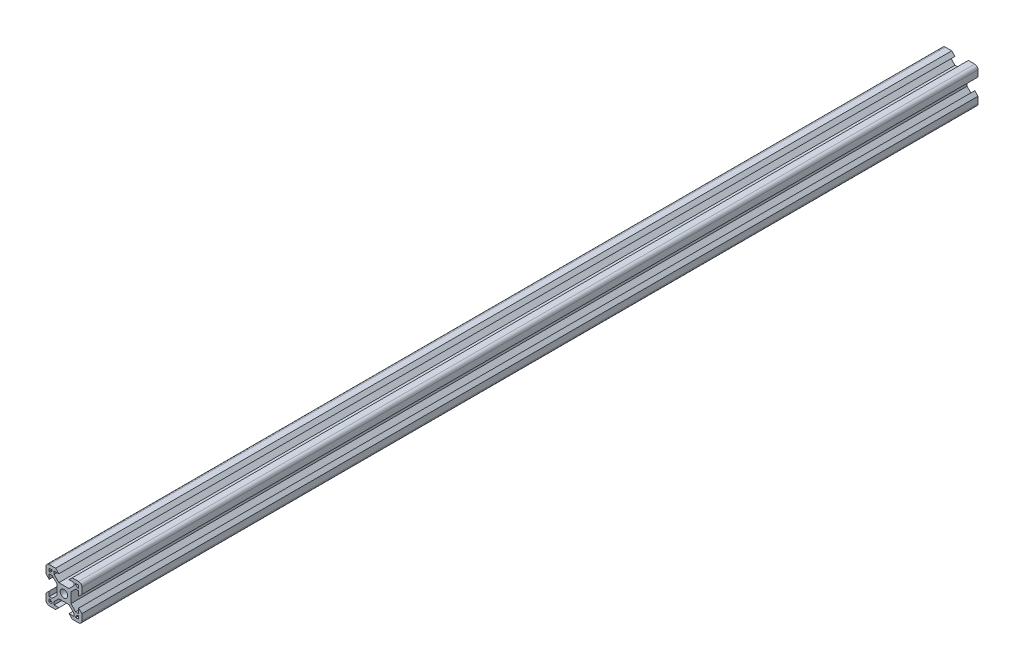
SolidWorks part; units mm, degrees
material "5052-H38, Barre (SS)"
ref_plane "Plan de face" through (0, 0, 0) normal (0, 0, 1) x (1, 0, 0)
ref_plane "Plan de dessus" through (0, 0, 0) normal (0, 1, 0) x (1, 0, 0)
ref_plane "Plan de droite" through (0, 0, 0) normal (1, 0, 0) x (0, 0, -1)
sketch "Esquisse1" plane through (0, 0, 0) normal (0, 0, 1) x (1, 0, 0)
  line L0 (-3.9007, 0) -> (-3.9007, -2.84)
  line L1 (-3.9007, -2.84) -> (-6.56, -5.4993)
  line L2 (-6.56, -5.4993) -> (-8.2, -5.4993)
  line L3 (-8.2, -5.4993) -> (-8.2, -2.84)
  line L4 (-8.2, -2.84) -> (-10, -4.64)
  line L5 (-10, -4.64) -> (-10, -8.2)
  line L6 (0, 0) -> (-17.0509, -17.0509) construction
  line L7 (0, 0) -> (0, -17.0509) construction
  line L8 (0, 0) -> (-30.3777, 0) construction
  line L9 (-4.64, -10) -> (-8.2, -10)
  line L10 (-2.84, -8.2) -> (-4.64, -10)
  line L11 (-5.4993, -8.2) -> (-2.84, -8.2)
  line L12 (-5.4993, -6.56) -> (-5.4993, -8.2)
  line L13 (-2.84, -3.9007) -> (-5.4993, -6.56)
  line L14 (0, -3.9007) -> (-2.84, -3.9007)
  line L15 (-8.2, -8.2) -> (-8.2, -6.5693)
  line L16 (-8.2, -6.5693) -> (-7.63, -6.5693)
  line L17 (-7.63, -6.5693) -> (-6.5693, -7.63)
  line L18 (-6.5693, -7.63) -> (-6.5693, -8.2)
  line L19 (-6.5693, -8.2) -> (-8.2, -8.2)
  line L20 (-3.9007, 0) -> (-3.9007, 2.84)
  line L21 (-3.9007, 2.84) -> (-6.56, 5.4993)
  line L22 (-6.56, 5.4993) -> (-8.2, 5.4993)
  line L23 (-8.2, 5.4993) -> (-8.2, 2.84)
  line L24 (-8.2, 2.84) -> (-10, 4.64)
  line L25 (-10, 4.64) -> (-10, 8.2)
  line L26 (-4.64, 10) -> (-8.2, 10)
  line L27 (-2.84, 8.2) -> (-4.64, 10)
  line L28 (-5.4993, 8.2) -> (-2.84, 8.2)
  line L29 (-5.4993, 6.56) -> (-5.4993, 8.2)
  line L30 (-2.84, 3.9007) -> (-5.4993, 6.56)
  line L31 (0, 3.9007) -> (-2.84, 3.9007)
  line L32 (-8.2, 6.5693) -> (-8.2, 8.2)
  line L33 (-8.2, 8.2) -> (-6.5693, 8.2)
  line L34 (-6.5693, 8.2) -> (-6.5693, 7.63)
  line L35 (-6.5693, 7.63) -> (-7.63, 6.5693)
  line L36 (-7.63, 6.5693) -> (-8.2, 6.5693)
  line L37 (0, 3.9007) -> (2.84, 3.9007)
  line L38 (2.84, 3.9007) -> (5.4993, 6.56)
  line L39 (5.4993, 6.56) -> (5.4993, 8.2)
  line L40 (5.4993, 8.2) -> (2.84, 8.2)
  line L41 (2.84, 8.2) -> (4.64, 10)
  line L42 (4.64, 10) -> (8.2, 10)
  line L43 (10, 4.64) -> (10, 8.2)
  line L44 (8.2, 2.84) -> (10, 4.64)
  line L45 (8.2, 5.4993) -> (8.2, 2.84)
  line L46 (6.56, 5.4993) -> (8.2, 5.4993)
  line L47 (3.9007, 2.84) -> (6.56, 5.4993)
  line L48 (3.9007, 0) -> (3.9007, 2.84)
  line L49 (6.5693, 8.2) -> (8.2, 8.2)
  line L50 (8.2, 8.2) -> (8.2, 6.5693)
  line L51 (8.2, 6.5693) -> (7.63, 6.5693)
  line L52 (7.63, 6.5693) -> (6.5693, 7.63)
  line L53 (6.5693, 7.63) -> (6.5693, 8.2)
  line L54 (3.9007, 0) -> (3.9007, -2.84)
  line L55 (3.9007, -2.84) -> (6.56, -5.4993)
  line L56 (6.56, -5.4993) -> (8.2, -5.4993)
  line L57 (8.2, -5.4993) -> (8.2, -2.84)
  line L58 (8.2, -2.84) -> (10, -4.64)
  line L59 (10, -4.64) -> (10, -8.2)
  line L60 (4.64, -10) -> (8.2, -10)
  line L61 (2.84, -8.2) -> (4.64, -10)
  line L62 (5.4993, -8.2) -> (2.84, -8.2)
  line L63 (5.4993, -6.56) -> (5.4993, -8.2)
  line L64 (2.84, -3.9007) -> (5.4993, -6.56)
  line L65 (0, -3.9007) -> (2.84, -3.9007)
  line L66 (8.2, -6.5693) -> (8.2, -8.2)
  line L67 (8.2, -8.2) -> (6.5693, -8.2)
  line L68 (6.5693, -8.2) -> (6.5693, -7.63)
  line L69 (6.5693, -7.63) -> (7.63, -6.5693)
  line L70 (7.63, -6.5693) -> (8.2, -6.5693)
  circle A0 centre (0, 0) radius 2.1
  arc A1 (-10, -8.2) -> (-8.2, -10) centre (-8.2, -8.2) ccw
  arc A2 (-8.2, 10) -> (-10, 8.2) centre (-8.2, 8.2) ccw
  arc A3 (10, 8.2) -> (8.2, 10) centre (8.2, 8.2) ccw
  arc A4 (8.2, -10) -> (10, -8.2) centre (8.2, -8.2) ccw
  point P23 (-7.0997, -7.0997)
  dimension "D4" = 4.2
  dimension "D1" = 45
  dimension "D2" = 5.68
  dimension "D3" = 1.64
  dimension "D5" = 1.5
  dimension "D6" = 20
  dimension "D7" = 1.8
  dimension "D8" = 1.07
  dimension "D9" = 4
extrude "Boss.-Extru.2" add sketch "Esquisse1" along normal mid plane 500
